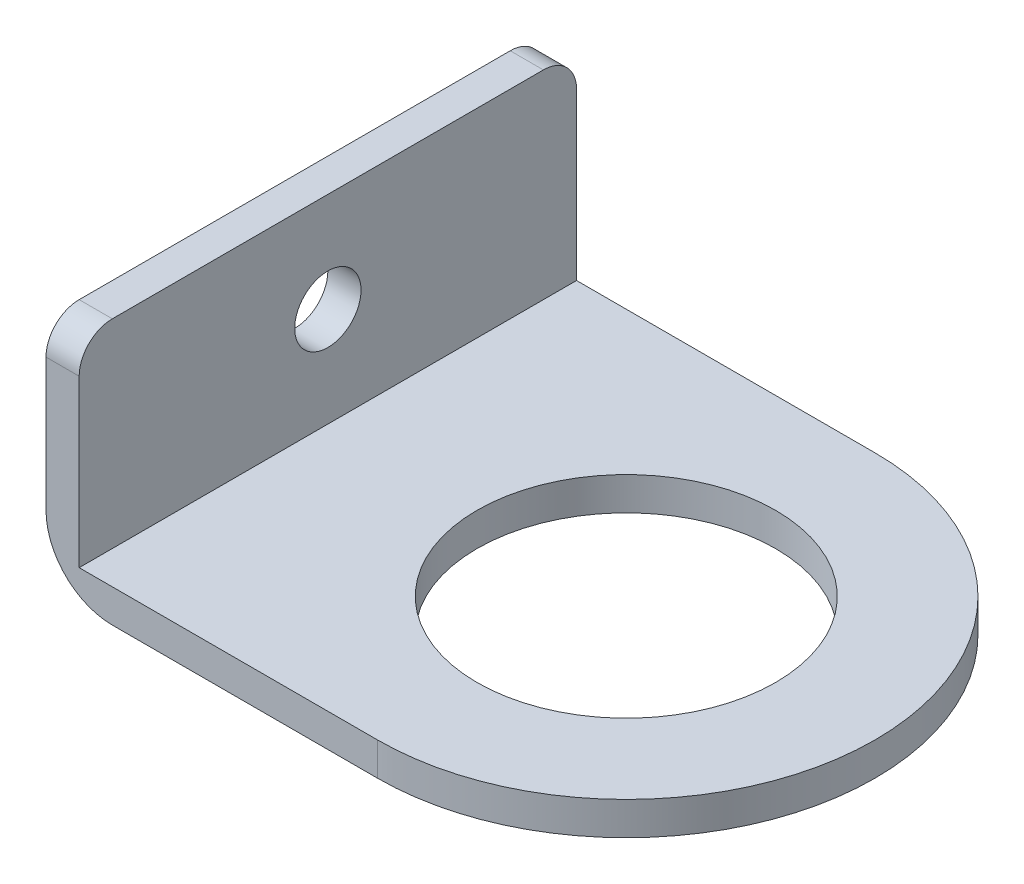
SolidWorks part; units mm, degrees
ref_plane "Front Plane" through (0, 0, 0) normal (0, 0, 1) x (1, 0, 0)
ref_plane "Top Plane" through (0, 0, 0) normal (0, 1, 0) x (1, 0, 0)
ref_plane "Right Plane" through (0, 0, 0) normal (1, 0, 0) x (0, 0, -1)
sketch "Sketch1" plane through (0, 0, 0) normal (0, 0, 1) x (1, 0, 0)
  line L0 (0, 0) -> (20, 0)
  line L1 (55, 0) -> (-55, 0) construction
  line L2 (20, 0) -> (20, 2)
  line L3 (20, 2) -> (2, 2)
  line L4 (2, 2) -> (2, 14)
  line L5 (2, 14) -> (0, 14)
  line L6 (0, -55) -> (0, 55) construction
  line L7 (0, 14) -> (0, 0)
  dimension "D1" = 14
  dimension "D2" = 2
  dimension "D3" = 2
  dimension "D4" = 20
extrude "Boss-Extrude1" add sketch "Sketch1" against normal blind 30
sketch "Sketch2" plane through (0, 0, 0) normal (0, 1, 0) x (1, 0, 0)
  line L0 (-7.7, 0) -> (7.7, 0) construction
  line L1 (20, 30) -> (20, 0) construction
  arc A0 (20, 30) -> (20, 0) centre (20, 15) cw
extrude "Extrude-Thin1" add sketch "Sketch2" along normal blind 2 thin
sketch "Sketch3" plane through (0, 2, 0) normal (0, 1, 0) x (1, 0, 0)
  line L1 (20, 20) -> (20, 10) construction
  circle A1 centre (20, 15) radius 9
extrude "Cut-Extrude1" cut sketch "Sketch3" against normal through all
fillet "Fillet2" radius 4 1 edges at (0, 0, -15)
ref_plane "Plane1" through (0, 0, 0) normal (1, 0, 0) x (0, 0, -1)
sketch "Sketch4" plane through (0, 0, 0) normal (1, 0, 0) x (0, 0, -1)
  line L0 (0, 14) -> (30, 2) construction
  line L1 (30, 2) -> (30, 14) construction
  line L2 (30, 14) -> (0, 2) construction
  line L3 (0, 7.7) -> (0, -7.7) construction
  line L4 (30, 2) -> (0, 2) construction
  circle A0 centre (15, 8) radius 2
extrude "Cut-Extrude2" cut sketch "Sketch4" against normal through all and the other way through all
fillet "Fillet3" radius 2 2 edges at (1, 14, -30) (1, 14, 0)
